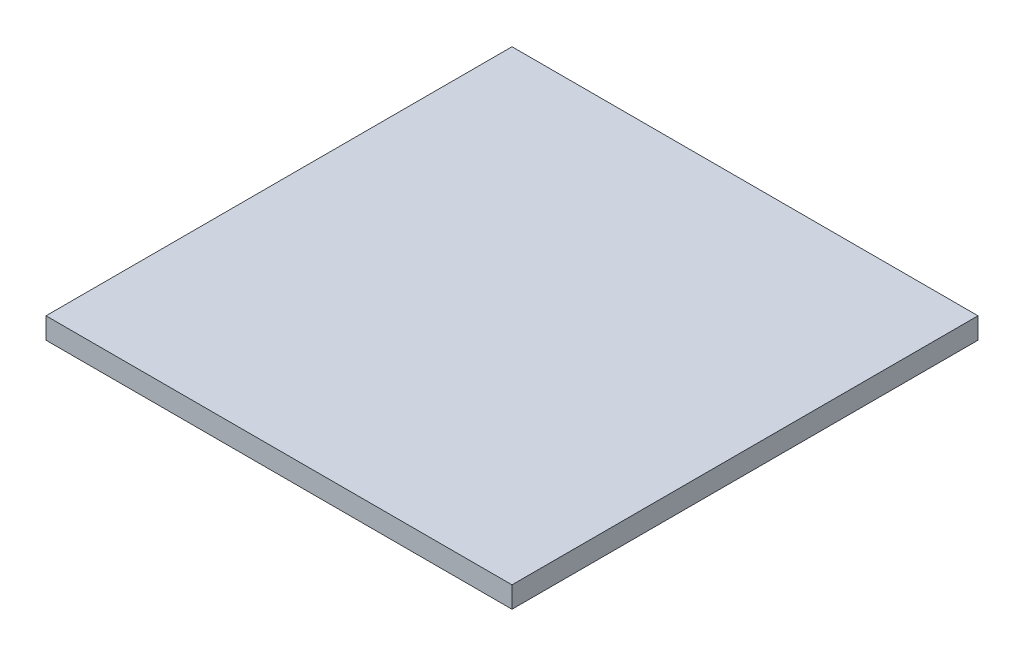
SolidWorks part; units mm, degrees
material "Acrílico (médio-alto impacto)"
ref_plane "Plano frontal" through (0, 0, 0) normal (0, 0, 1) x (1, 0, 0)
ref_plane "Plano superior" through (0, 0, 0) normal (0, 1, 0) x (1, 0, 0)
ref_plane "Plano direito" through (0, 0, 0) normal (1, 0, 0) x (0, 0, -1)
sketch "Esboço1" plane through (0, 0, 0) normal (0, 1, 0) x (1, 0, 0)
  line L1 (-27.5, -27.5) -> (27.5, -27.5)
  line L2 (-27.5, -27.5) -> (-27.5, 27.5)
  line L3 (-27.5, 27.5) -> (27.5, 27.5)
  line L4 (27.5, -27.5) -> (27.5, 27.5)
  line L5 (-27.5, -27.5) -> (27.5, 27.5) construction
  line L6 (-27.5, 27.5) -> (27.5, -27.5) construction
  point P0 (0, 0)
  dimension "D1" = 90
  dimension "D2" = 55
extrude "Ressalto-extrusão1" add sketch "Esboço1" along normal blind 2
sketch "Esboço3" plane through (0, 0, 0) normal (0, -1, 0) x (1, 0, 0)
  line L1 (-27.5, -27.5) -> (27.5, -27.5)
  line L2 (-27.5, -27.5) -> (-27.5, 27.5)
  line L3 (-27.5, 27.5) -> (27.5, 27.5)
  line L4 (27.5, -27.5) -> (27.5, 27.5)
  line L5 (-27.5, -27.5) -> (27.5, 27.5) construction
  line L6 (-27.5, 27.5) -> (27.5, -27.5) construction
  circle A0 centre (0, 0) radius 25
  point P0 (0, 0)
  dimension "D1" = 50
extrude "Ressalto-extrusão3" add sketch "Esboço3" along normal blind 0.5
